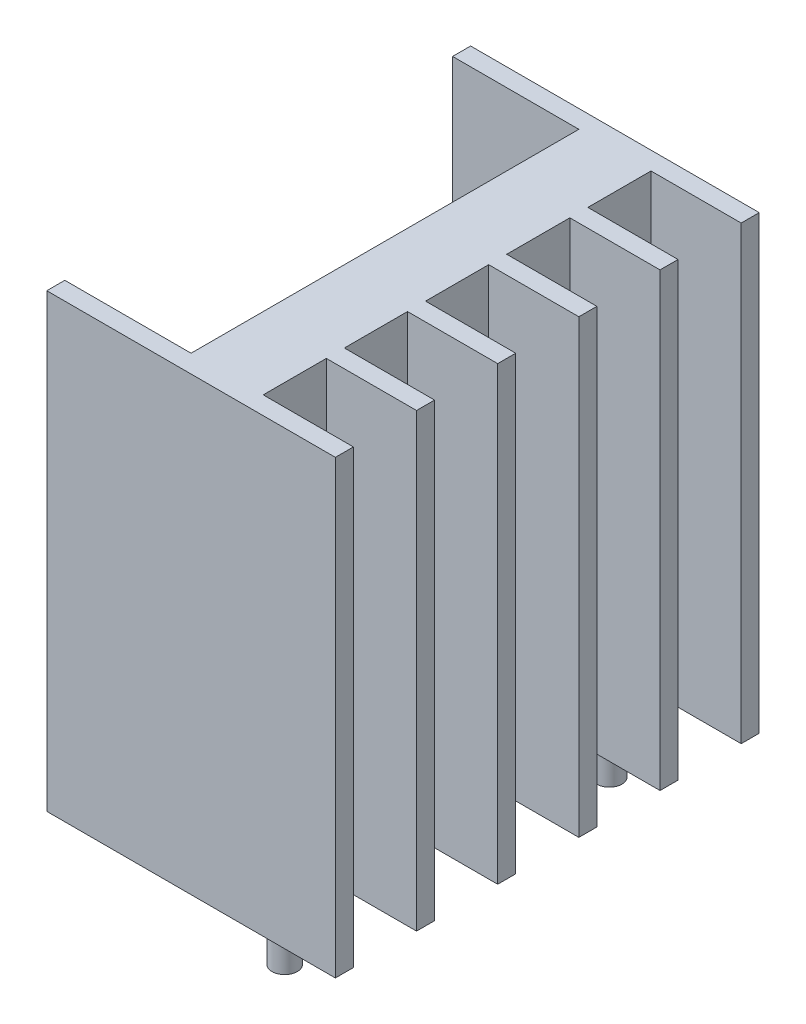
SolidWorks part; units mm, degrees
ref_plane "Front Plane" through (0, 0, 0) normal (0, 0, 1) x (1, 0, 0)
ref_plane "Top Plane" through (0, 0, 0) normal (0, 1, 0) x (1, 0, 0)
ref_plane "Right Plane" through (0, 0, 0) normal (1, 0, 0) x (0, 0, -1)
sketch "Sketch1" plane through (0, 0, 0) normal (0, 1, 0) x (1, 0, 0)
  line L1 (-2, 11.75) -> (2, 11.75)
  line L2 (-2, 11.75) -> (-2, -11.75)
  line L3 (-2, -11.75) -> (2, -11.75)
  line L4 (2, 11.75) -> (2, -11.75)
  line L5 (-2, 11.75) -> (2, -11.75) construction
  line L6 (-2, -11.75) -> (2, 11.75) construction
  point P0 (0, 0)
  dimension "D1" = 23.5
  dimension "D2" = 4
extrude "Boss-Extrude1" add sketch "Sketch1" along normal blind 25
sketch "Sketch2" plane through (0, 25, 0) normal (0, 1, 0) x (1, 0, 0)
  line L0 (2, -11.75) -> (2, 11.75) construction
  line L1 (2, -11.75) -> (7, -11.75)
  line L2 (2, -11.75) -> (2, -10.75)
  line L3 (2, -10.75) -> (7, -10.75)
  line L4 (7, -11.75) -> (7, -10.75)
  line L5 (-2, -11.75) -> (-9, -11.75)
  line L6 (-2, -11.75) -> (-2, -10.75)
  line L7 (-2, -10.75) -> (-9, -10.75)
  line L8 (-9, -11.75) -> (-9, -10.75)
  line L9 (-2, 11.75) -> (-9, 11.75)
  line L10 (-2, 11.75) -> (-2, 10.75)
  line L11 (-2, 10.75) -> (-9, 10.75)
  line L12 (-9, 11.75) -> (-9, 10.75)
  line L13 (2, 11.75) -> (7, 11.75)
  line L14 (2, 11.75) -> (2, 10.75)
  line L15 (2, 10.75) -> (7, 10.75)
  line L16 (7, 11.75) -> (7, 10.75)
  line L17 (2, 7.25) -> (7, 7.25)
  line L18 (2, 7.25) -> (2, 6.25)
  line L19 (2, 6.25) -> (7, 6.25)
  line L20 (7, 7.25) -> (7, 6.25)
  line L21 (4.5, 6.25) -> (4.5, 2.75) construction
  line L22 (2, 2.75) -> (7, 2.75)
  line L23 (2, 2.75) -> (2, 1.75)
  line L24 (2, 1.75) -> (7, 1.75)
  line L25 (7, 2.75) -> (7, 1.75)
  line L26 (2, -1.75) -> (7, -1.75)
  line L27 (2, -1.75) -> (2, -2.75)
  line L28 (2, -2.75) -> (7, -2.75)
  line L29 (7, -1.75) -> (7, -2.75)
  line L30 (2, -6.25) -> (7, -6.25)
  line L31 (2, -6.25) -> (2, -7.25)
  line L32 (2, -7.25) -> (7, -7.25)
  line L33 (7, -6.25) -> (7, -7.25)
  line L34 (4.5, 10.75) -> (4.5, 7.25) construction
  line L35 (4.5, 1.75) -> (4.5, -1.75) construction
  line L37 (4.5, -2.75) -> (4.5, -6.25) construction
  line L39 (4.5, -7.25) -> (4.5, -10.75) construction
  dimension "D1" = 16
  dimension "D2" = 1
  dimension "D3" = 7
extrude "Boss-Extrude2" add sketch "Sketch2" against normal up to surface (25 mm away) up to face at (0, 0, 0)
sketch "Sketch3" plane through (-2, 0, 0) normal (-1, 0, 0) x (0, 0, 1)
  line L0 (0, 25) -> (0, 18) construction
  line L1 (-10.75, 25) -> (10.75, 25) construction
  line L2 (-10.75, 0) -> (10.75, 0) construction
  circle A0 centre (0, 18) radius 1.6
  dimension "D1" = 18
  dimension "D2" = 3.2
extrude "Cut-Extrude1" cut sketch "Sketch3" against normal blind 25
sketch "Sketch4" plane through (0, 0, 0) normal (0, -1, 0) x (1, 0, 0)
  line L0 (-2, 0) -> (1.4388, 0) construction
  line L1 (-2, -10.75) -> (-2, 10.75) construction
  line L2 (1.4388, 0) -> (1.4388, -9) construction
  line L3 (1.4388, 0) -> (1.4388, 9) construction
  circle A0 centre (1.4388, 9) radius 0.7
  circle A1 centre (1.4388, -9) radius 0.7
  point P9 (1.4388, 0)
  dimension "D2" = 1.4
  dimension "D1" = 18
extrude "Boss-Extrude3" add sketch "Sketch4" along normal blind 3.5
